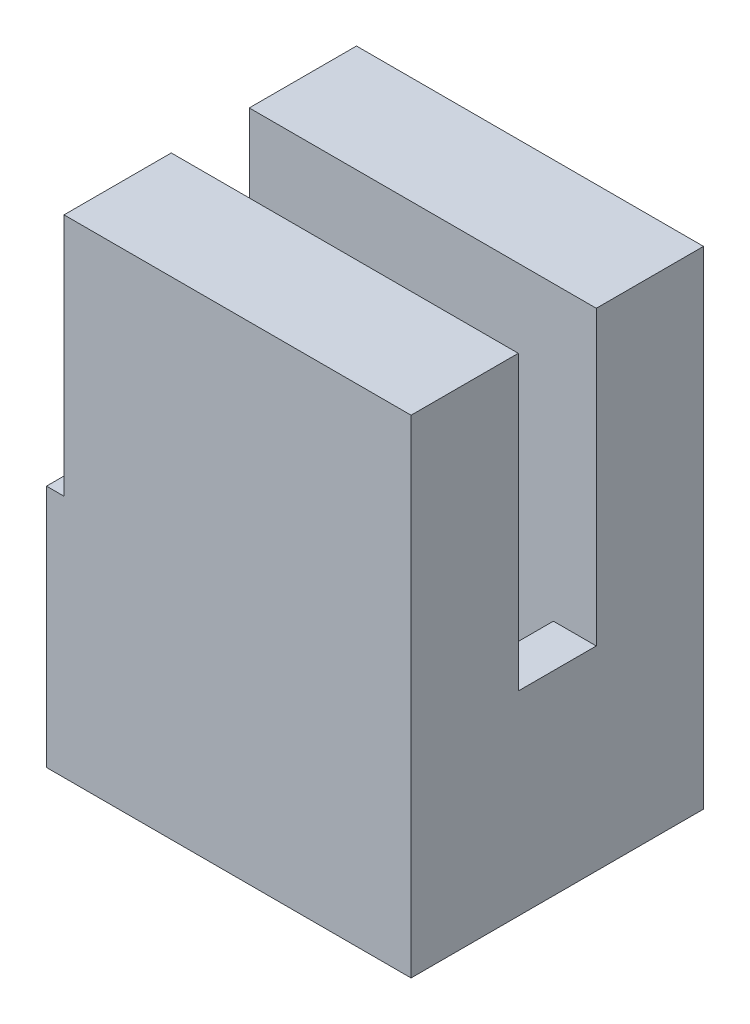
SolidWorks part; units mm, degrees
ref_plane "Front Plane" through (0, 0, 0) normal (0, 0, 1) x (1, 0, 0)
ref_plane "Top Plane" through (0, 0, 0) normal (0, 1, 0) x (1, 0, 0)
ref_plane "Right Plane" through (0, 0, 0) normal (1, 0, 0) x (0, 0, -1)
sketch "Sketch1" plane through (0, 0, 0) normal (0, 1, 0) x (1, 0, 0)
  line L1 (-23.749, 19.05) -> (23.749, 19.05)
  line L2 (-23.749, 19.05) -> (-23.749, -19.05)
  line L3 (-23.749, -19.05) -> (23.749, -19.05)
  line L4 (23.749, 19.05) -> (23.749, -19.05)
  line L5 (-23.749, 19.05) -> (23.749, -19.05) construction
  line L6 (-23.749, -19.05) -> (23.749, 19.05) construction
  point P0 (0, 0)
  dimension "D1" = 38.1
  dimension "D2" = 47.498
extrude "Boss-Extrude1" add sketch "Sketch1" along normal blind 63.5
sketch "Sketch3" plane through (0, 63.5, 0) normal (0, 1, 0) x (1, 0, 0)
  line L0 (23.749, -19.05) -> (23.749, 19.05) construction
  line L1 (-23.749, 5.08) -> (23.749, 5.08)
  line L2 (-23.749, 5.08) -> (-23.749, -5.08)
  line L3 (-23.749, -5.08) -> (23.749, -5.08)
  line L4 (23.749, 5.08) -> (23.749, -5.08)
  line L5 (-23.749, 5.08) -> (23.749, -5.08) construction
  line L6 (-23.749, -5.08) -> (23.749, 5.08) construction
  point P0 (0, 0)
  dimension "D1" = 10.16
extrude "Cut-Extrude1" cut sketch "Sketch3" against normal blind 38.1
sketch "Sketch4" plane through (0, 0, 0) normal (0, -1, 0) x (1, 0, 0)
  line L0 (-23.749, -19.05) -> (-23.749, 19.05) construction
  line L1 (-23.749, -8.5725) -> (18.161, -8.5725)
  line L2 (-23.749, -8.5725) -> (-23.749, 8.5725)
  line L3 (-23.749, 8.5725) -> (18.161, 8.5725)
  line L4 (18.161, -8.5725) -> (18.161, 8.5725)
  line L5 (-23.749, -8.5725) -> (18.161, 8.5725) construction
  line L6 (-23.749, 8.5725) -> (18.161, -8.5725) construction
  line L7 (23.749, 19.05) -> (23.749, -19.05) construction
  line L8 (-23.749, 8.5725) -> (-23.749, 19.05) construction
  line L9 (-23.749, -8.5725) -> (-23.749, -19.05) construction
  point P0 (-2.794, 0)
  dimension "D1" = 17.145
  dimension "D2" = 5.588
extrude "Cut-Extrude2" cut sketch "Sketch4" against normal offset from surface (19.05 mm away) 6.35 up to face at (0, 25.4, 0)
sketch "Sketch5" plane through (0, 25.4, 0) normal (0, 1, 0) x (1, 0, 0)
  line L1 (-21.971, -5.08) -> (18.161, -5.08)
  line L2 (-21.971, -5.08) -> (-21.971, 5.08)
  line L3 (-21.971, 5.08) -> (18.161, 5.08)
  line L4 (18.161, -5.08) -> (18.161, 5.08)
  line L5 (-21.971, -5.08) -> (18.161, 5.08) construction
  line L6 (-21.971, 5.08) -> (18.161, -5.08) construction
  line L7 (-21.971, 5.08) -> (-23.749, 5.08) construction
  line L8 (23.749, -5.08) -> (23.749, 5.08) construction
  point P0 (-1.905, 0)
  dimension "D1" = 1.778
  dimension "D2" = 5.588
extrude "Cut-Extrude3" cut sketch "Sketch5" against normal through all
sketch "Sketch6" plane through (0, 63.5, 0) normal (0, 1, 0) x (1, 0, 0)
  line L0 (-23.749, -19.05) -> (23.749, -19.05) construction
  line L1 (15.113, 19.05) -> (9.525, 19.05)
  line L2 (15.113, 19.05) -> (15.113, -19.05)
  line L3 (15.113, -19.05) -> (9.525, -19.05)
  line L4 (9.525, 19.05) -> (9.525, -19.05)
  line L6 (-23.749, 19.05) -> (-21.463, 19.05)
  line L7 (-23.749, 19.05) -> (-23.749, -19.05)
  line L8 (-23.749, -19.05) -> (-21.463, -19.05)
  line L9 (-21.463, 19.05) -> (-21.463, -19.05)
  line L12 (23.749, 19.05) -> (-23.749, 19.05) construction
  dimension "D1" = 5.588
  dimension "D2" = 2.286
  dimension "D3" = 30.988
extrude "Cut-Extrude4" cut sketch "Sketch6" against normal offset from surface (31.75 mm away) 6.35 contours L7 L6 L9 L8 up to face at (-22.86, 25.4, 0)
